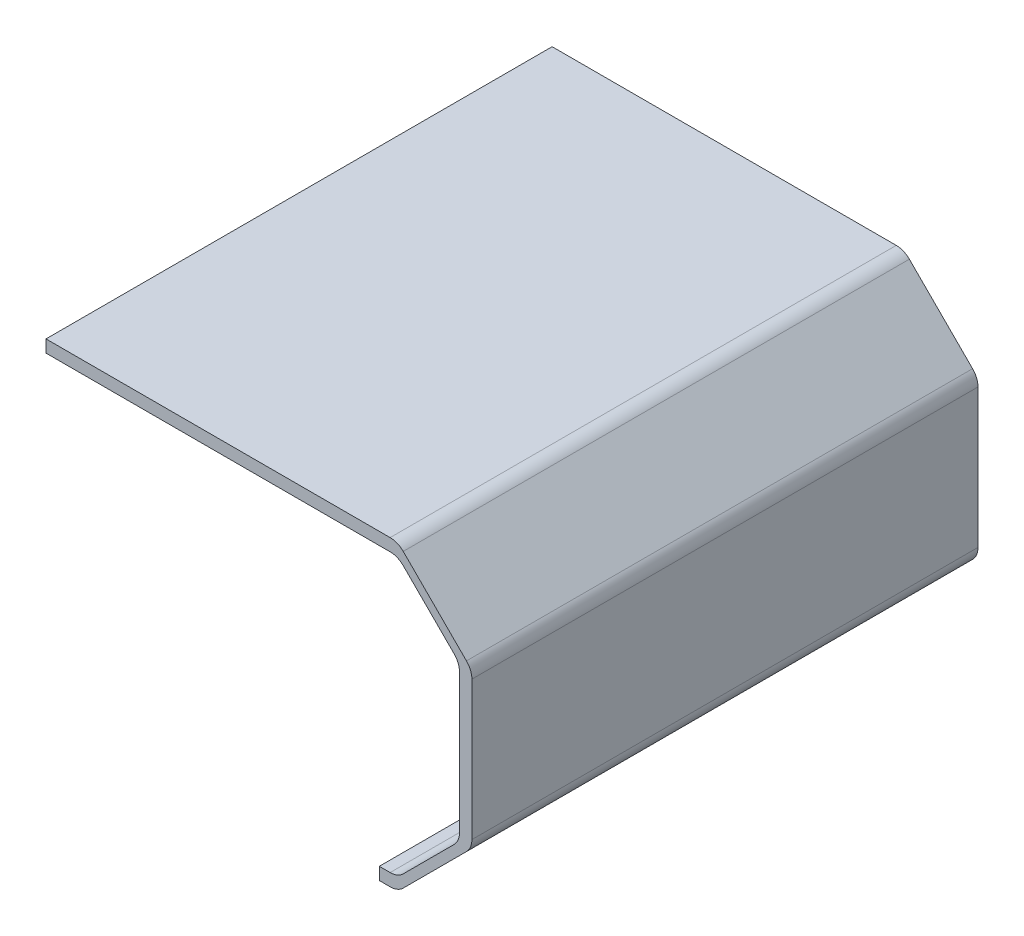
SolidWorks part; units mm, degrees
ref_plane "前视基准面" through (0, 0, 0) normal (0, 0, 1) x (1, 0, 0)
ref_plane "上视基准面" through (0, 0, 0) normal (0, 1, 0) x (1, 0, 0)
ref_plane "右视基准面" through (0, 0, 0) normal (1, 0, 0) x (0, 0, -1)
sketch "草图1" plane through (0, 0, 0) normal (0, 0, 1) x (1, 0, 0)
  line L0 (0, 0) -> (0, 2)
  line L1 (0, 2) -> (3, 2)
  line L5 (-54, 49) -> (3, 49)
  line L7 (0, 0) -> (3, 0)
  line L13 (3, 47) -> (-54, 47)
  line L15 (3, 2) -> (13, 12)
  line L16 (3, 0) -> (15, 12)
  line L17 (13, 37) -> (13, 12)
  line L18 (15, 12) -> (15, 37)
  line L19 (3, 47) -> (13, 37)
  line L20 (3, 49) -> (15, 37)
  line L21 (-54, 49) -> (-54, 47)
  point P5 (0, 0)
extrude "凸台-拉伸1" add sketch "草图1" along normal blind 82
fillet "圆角1" radius 3 8 edges at (3, 0, 41) (15, 12, 41) (15, 37, 41) (3, 49, 41) (3, 2, 41) (13, 12, 41) (13, 37, 41) (3, 47, 41)
